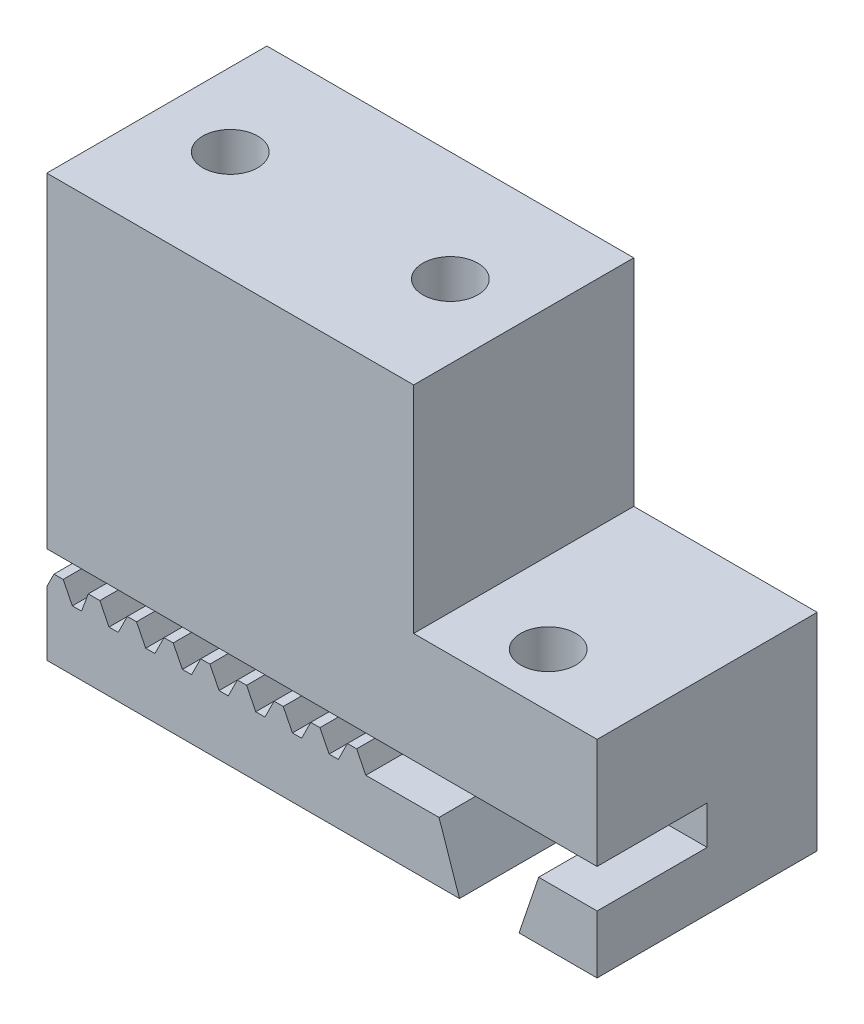
SolidWorks part; units mm, degrees
ref_plane "前视基准面" through (0, 0, 0) normal (0, 0, 1) x (1, 0, 0)
ref_plane "上视基准面" through (0, 0, 0) normal (0, 1, 0) x (1, 0, 0)
ref_plane "右视基准面" through (0, 0, 0) normal (1, 0, 0) x (0, 0, -1)
sketch "草图2" plane through (0, 0, 0) normal (0, 0, 1) x (1, 0, 0)
  line L1 (0, 0) -> (30, 0)
  line L2 (0, 0) -> (0, 23)
  line L3 (0, 23) -> (30, 23)
  line L4 (30, 0) -> (30, 23)
  dimension "D1" = 23
  dimension "D2" = 30
extrude "凸台-拉伸1" add sketch "草图2" along normal blind 12
sketch "草图3" plane through (0, 0, 12) normal (0, 0, 1) x (1, 0, 0)
  line L1 (-0.1065, 5.265) -> (32.1377, 5.265)
  line L2 (26.8147, 3.165) -> (25.6215, -0.3645)
  line L3 (25.6215, -0.3645) -> (22.6215, -0.3645)
  line L4 (22.6215, -0.3645) -> (21.3828, 3.2732)
  line L5 (17.3913, 3.265) -> (21.3828, 3.2732)
  line L6 (26.8147, 3.165) -> (32.1377, 3.165)
  line L45 (1.6432, 3.424) -> (1.6432, 4.2129) construction
  line L47 (0.6434, 4.424) -> (0.6434, 3.7449) construction
  line L52 (32.1377, 3.165) -> (32.1377, 5.265)
  line L54 (16.8914, 4.265) -> (17.3913, 3.265)
  line L55 (16.3914, 4.265) -> (16.8914, 4.265)
  line L56 (15.8916, 3.265) -> (16.3914, 4.265)
  line L57 (15.3916, 3.265) -> (15.8916, 3.265)
  line L58 (14.8917, 4.265) -> (15.3916, 3.265)
  line L59 (14.3917, 4.265) -> (14.8917, 4.265)
  line L60 (13.8918, 3.265) -> (14.3917, 4.265)
  line L61 (13.3918, 3.265) -> (13.8918, 3.265)
  line L62 (12.8919, 4.265) -> (13.3918, 3.265)
  line L63 (12.3919, 4.265) -> (12.8919, 4.265)
  line L64 (11.892, 3.265) -> (12.3919, 4.265)
  line L65 (11.392, 3.265) -> (11.892, 3.265)
  line L66 (10.8922, 4.265) -> (11.392, 3.265)
  line L67 (10.3922, 4.265) -> (10.8922, 4.265)
  line L68 (9.8923, 3.265) -> (10.3922, 4.265)
  line L70 (9.3923, 3.265) -> (9.8923, 3.265)
  line L71 (8.8924, 4.265) -> (9.3923, 3.265)
  line L72 (8.3924, 4.265) -> (8.8924, 4.265)
  line L73 (7.8925, 3.265) -> (8.3924, 4.265)
  line L74 (7.3925, 3.265) -> (7.8925, 3.265)
  line L75 (6.8926, 4.265) -> (7.3925, 3.265)
  line L76 (6.3926, 4.265) -> (6.8926, 4.265)
  line L77 (5.8928, 3.265) -> (6.3926, 4.265)
  line L78 (5.3928, 3.265) -> (5.8928, 3.265)
  line L79 (4.8929, 4.265) -> (5.3928, 3.265)
  line L80 (4.3929, 4.265) -> (4.8929, 4.265)
  line L81 (3.893, 3.265) -> (4.3929, 4.265)
  line L82 (3.393, 3.265) -> (3.893, 3.265)
  line L83 (2.8931, 4.265) -> (3.393, 3.265)
  line L84 (2.2606, 4.265) -> (2.8931, 4.265)
  line L85 (1.8932, 3.265) -> (2.2606, 4.265)
  line L86 (1.3932, 3.265) -> (1.8932, 3.265)
  line L87 (0.8934, 4.265) -> (1.3932, 3.265)
  line L88 (0.3934, 4.265) -> (0.8934, 4.265)
  line L89 (-0.1065, 3.265) -> (0.3934, 4.265)
  line L92 (-0.1065, 3.265) -> (-0.1065, 5.265)
  dimension "D1" = 2.1
  dimension "D2" = 3
  dimension "D3" = 1
extrude "切除-拉伸1" cut sketch "草图3" against normal blind 6
sketch "草图4" plane through (0, 0, 12) normal (0, 0, 1) x (1, 0, 0)
  line L0 (0, 23) -> (0, 5.265) construction
  line L1 (20, 25.2522) -> (35.4673, 25.2522)
  line L2 (20, 25.2522) -> (20, 11.265)
  line L3 (20, 11.265) -> (35.4673, 11.265)
  line L4 (35.4673, 25.2522) -> (35.4673, 11.265)
  line L6 (0, 5.265) -> (30, 5.265) construction
  dimension "D1" = 20
  dimension "D2" = 6
extrude "切除-拉伸2" cut sketch "草图4" against normal through all
sketch "草图5" plane through (0, 11.265, 0) normal (0, 1, 0) x (1, 0, 0)
  circle A0 centre (24.4102, -9.0758) radius 1.5
  dimension "D1" = 3
extrude "切除-拉伸3" cut sketch "草图5" against normal blind 8
sketch "草图6" plane through (0, 23, 0) normal (0, 1, 0) x (1, 0, 0)
  line L0 (10, 0) -> (10, -4.2992) construction
  line L5 (20, 0) -> (0, 0) construction
  line L6 (0, -12) -> (0, 0) construction
  circle A0 centre (4, -6) radius 1.5
  circle A1 centre (16, -6) radius 1.5
  dimension "D1" = 3
  dimension "D2" = 10
  dimension "D3" = 6
  dimension "D4" = 4
extrude "切除-拉伸4" cut sketch "草图6" against normal blind 12
